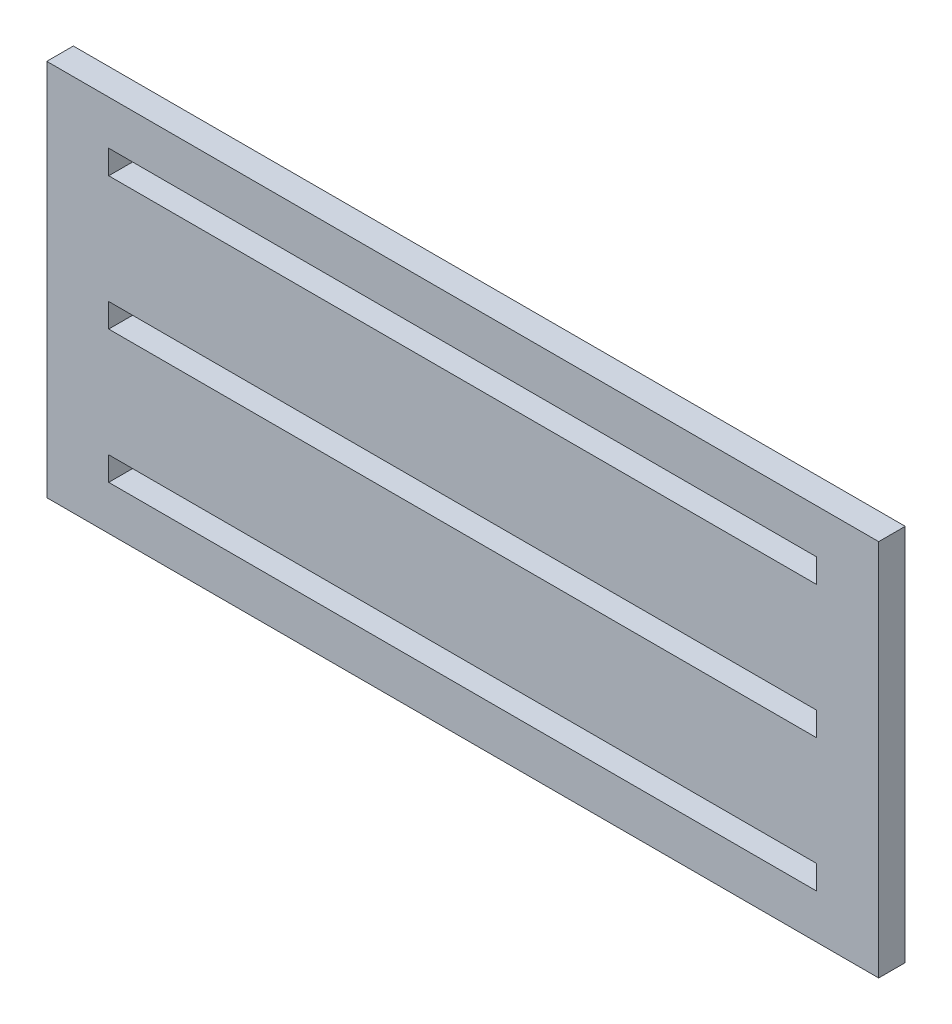
SolidWorks part; units mm, degrees
ref_plane "前基準面" through (0, 0, 0) normal (0, 0, 1) x (1, 0, 0)
ref_plane "上基準面" through (0, 0, 0) normal (0, 1, 0) x (1, 0, 0)
ref_plane "右基準面" through (0, 0, 0) normal (1, 0, 0) x (0, 0, -1)
sketch "草圖1" plane through (0, 0, 0) normal (0, 0, 1) x (1, 0, 0)
  line L0 (-6.3322, -4.4609) -> (73.6678, -4.4609) construction
  line L1 (-6.3322, -3.1109) -> (73.6678, -3.1109)
  line L2 (-6.3322, -3.1109) -> (-6.3322, -5.8109)
  line L3 (-6.3322, -5.8109) -> (73.6678, -5.8109)
  line L4 (73.6678, -3.1109) -> (73.6678, -5.8109)
  line L5 (-13.3322, -25.8109) -> (80.6678, -25.8109)
  line L6 (-13.3322, -25.8109) -> (-13.3322, 16.8891)
  line L7 (-13.3322, 16.8891) -> (80.6678, 16.8891)
  line L8 (80.6678, -25.8109) -> (80.6678, 16.8891)
  line L9 (-6.3322, 9.1891) -> (73.6678, 9.1891)
  line L10 (-6.3322, 9.1891) -> (-6.3322, 11.8891)
  line L11 (-6.3322, 11.8891) -> (73.6678, 11.8891)
  line L12 (73.6678, 9.1891) -> (73.6678, 11.8891)
  line L13 (-6.3322, -20.8109) -> (73.6678, -20.8109)
  line L14 (73.6678, -18.1109) -> (73.6678, -20.8109)
  line L15 (-6.3322, -18.1109) -> (73.6678, -18.1109)
  line L16 (-6.3322, -18.1109) -> (-6.3322, -20.8109)
  line L17 (-6.3322, 10.5391) -> (73.6678, 10.5391) construction
  point P8 (80.6678, -4.4609)
  dimension "D1" = 2.7
  dimension "D2" = 80
  dimension "D3" = 7
  dimension "D4" = 7
  dimension "D5" = 2.7
  dimension "D6" = 80
  dimension "D7" = 15
  dimension "D8" = 5
  dimension "D9" = 5
  dimension "D10" = 94
extrude "填料-伸長1" add sketch "草圖1" along normal blind 3
